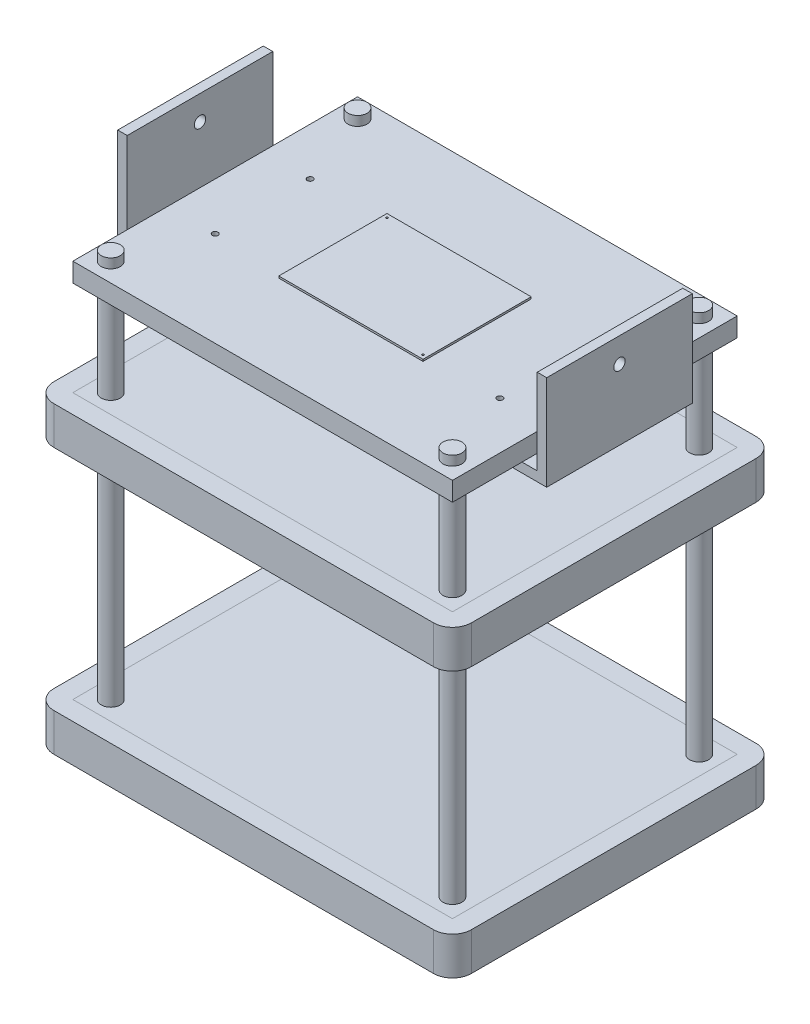
SolidWorks part; units mm, degrees
ref_plane "Front Plane" through (0, 0, 0) normal (0, 0, 1) x (1, 0, 0)
ref_plane "Top Plane" through (0, 0, 0) normal (0, 1, 0) x (1, 0, 0)
ref_plane "Right Plane" through (0, 0, 0) normal (1, 0, 0) x (0, 0, -1)
sketch "Sketch1" plane through (0, 0, 0) normal (0, 1, 0) x (1, 0, 0)
  line L1 (-100, 75) -> (100, 75)
  line L2 (-100, 75) -> (-100, -75)
  line L3 (-100, -75) -> (100, -75)
  line L4 (100, 75) -> (100, -75)
  line L5 (-100, 75) -> (100, -75) construction
  line L6 (-100, -75) -> (100, 75) construction
  point P0 (0, 0)
  dimension "D1" = 200
  dimension "D2" = 150
extrude "Boss-Extrude1" add sketch "Sketch1" along normal blind 10
sketch "Sketch2" plane through (0, 10, 0) normal (0, 1, 0) x (1, 0, 0)
  line L0 (-100, 75) -> (-100, -75) construction
  line L1 (100, 75) -> (-100, 75) construction
  line L2 (0, 73.0671) -> (0, 83.6614) construction
  line L3 (0, 83.6614) -> (0, -94.4748) construction
  line L4 (-110.8687, 0) -> (113.9791, 0) construction
  circle A0 centre (-90, 65) radius 5
  circle A1 centre (90, 65) radius 5
  circle A2 centre (90, -65) radius 5
  circle A3 centre (-90, -65) radius 5
  dimension "D1" = 10
  dimension "D2" = 10
  dimension "D3" = 10
extrude "Cut-Extrude1" cut sketch "Sketch2" against normal blind 10
ref_plane "Plane1" through (0, 140, 0) normal (0, 1, 0) x (1, 0, 0)
sketch "Sketch3" plane through (0, 140, 0) normal (0, 1, 0) x (1, 0, 0)
  line L1 (-100, 75) -> (100, 75)
  line L2 (-100, 75) -> (-100, -75)
  line L3 (-100, -75) -> (100, -75)
  line L4 (100, 75) -> (100, -75)
  line L5 (-100, 75) -> (100, -75) construction
  line L6 (-100, -75) -> (100, 75) construction
  circle A0 centre (-90, 65) radius 5
  circle A1 centre (90, 65) radius 5
  circle A2 centre (-90, -65) radius 5
  circle A3 centre (90, -65) radius 5
  point P0 (0, 0)
extrude "Boss-Extrude2" add sketch "Sketch3" along normal blind 10 separate body
ref_plane "Plane4" through (0, 200, 0) normal (0, 1, 0) x (1, 0, 0)
sketch "Sketch4" plane through (0, 200, 0) normal (0, 1, 0) x (1, 0, 0)
  line L1 (-100, 75) -> (100, 75)
  line L2 (-100, 75) -> (-100, -75)
  line L3 (-100, -75) -> (100, -75)
  line L4 (100, 75) -> (100, -75)
  line L5 (-100, 75) -> (100, -75) construction
  line L6 (-100, -75) -> (100, 75) construction
  circle A0 centre (-90, 65) radius 5
  circle A1 centre (90, 65) radius 5
  circle A2 centre (90, -65) radius 5
  circle A3 centre (-90, -65) radius 5
  point P1 (0, 0)
extrude "Boss-Extrude3" add sketch "Sketch4" along normal blind 10 separate body
sketch "Sketch5" plane through (0, 210, 0) normal (0, 1, 0) x (1, 0, 0)
  circle A0 centre (-90, -65) radius 5
sketch "Sketch17" plane through (0, 200, 0) normal (0, -1, 0) x (1, 0, 0)
  circle A0 centre (-90, -65) radius 5.3637
sketch "Sketch21" plane through (0, 10, 0) normal (0, 1, 0) x (1, 0, 0)
  circle A0 centre (-90, -65) radius 5
  circle A1 centre (-90, 65) radius 5
  circle A2 centre (90, 65) radius 5
  circle A3 centre (90, -65) radius 5
  dimension "D1" = 10
  dimension "D2" = 10
  dimension "D3" = 10
  dimension "D4" = 10
extrude "Boss-Extrude13" add sketch "Sketch21" along normal blind 205
sketch "Sketch22" plane through (0, 10, 0) normal (0, 1, 0) x (1, 0, 0)
  circle A0 centre (-90, 65) radius 5
  circle A1 centre (-90, -65) radius 5
  circle A2 centre (90, -65) radius 5
  circle A3 centre (90, 65) radius 5
  dimension "D1" = 10
  dimension "D2" = 10
  dimension "D3" = 10
  dimension "D4" = 10
extrude "Boss-Extrude14" add sketch "Sketch22" against normal blind 15
sketch "Sketch23" plane through (0, 210, 0) normal (0, 1, 0) x (1, 0, 0)
  line L0 (-100, 75) -> (-100, -75) construction
  line L1 (-140.155, 0) -> (119.4256, 0) construction
  line L2 (0, -82.5) -> (0, 82.5) construction
  circle A0 centre (-75, 25) radius 1.5
  circle A1 centre (-75, -25) radius 1.5
  circle A2 centre (75, -25) radius 1.5
  circle A3 centre (75, 25) radius 1.5
  dimension "D1" = 3
  dimension "D2" = 25
  dimension "D3" = 25
extrude "Cut-Extrude2" cut sketch "Sketch23" against normal blind 10
sketch "Sketch27" plane through (0, 210, 0) normal (0, 1, 0) x (1, 0, 0)
  line L0 (-38, 28.5) -> (38, -28.5) construction
  line L5 (-38, -28.5) -> (38, 28.5) construction
  line L7 (-38, 28.5) -> (38, 28.5)
  line L8 (-38, 28.5) -> (-38, -28.5)
  line L9 (-38, -28.5) -> (38, -28.5)
  line L10 (38, 28.5) -> (38, -28.5)
  circle A0 centre (-36, 26.5) radius 0.5
  circle A1 centre (36, -26.5) radius 0.5
  point P0 (-6.164, -10.787)
  point P5 (0, 0)
  point P11 (0, 0)
  dimension "D3" = 1
  dimension "D6" = 1
  dimension "D1" = 57
  dimension "D2" = 76
  dimension "D4" = 2
  dimension "D5" = 2
  dimension "D7" = 2
  dimension "D8" = 2
extrude "Boss-Extrude16" add sketch "Sketch27" along normal blind 1 contours L8 L7 L10 L9
sketch "Sketch30" plane through (0, 211, 0) normal (0, 1, 0) x (1, 0, 0)
  line L0 (-38, 28.5) -> (-38, -28.5) construction
  line L1 (-38, 28.5) -> (38, 28.5) construction
  line L2 (38, 28.5) -> (38, -28.5) construction
  line L3 (-38, -28.5) -> (38, -28.5) construction
  circle A0 centre (-36, 26.5) radius 0.5
  circle A1 centre (36, -26.5) radius 0.5
  dimension "D1" = 1
  dimension "D4" = 1
  dimension "D2" = 2
  dimension "D3" = 2
  dimension "D5" = 2
  dimension "D6" = 2
extrude "Cut-Extrude3" cut sketch "Sketch30" against normal blind 30
sketch "Sketch35" plane through (0, 0, 0) normal (0, -1, 0) x (-1, 0, 0)
  line L1 (100, -75) -> (-100, -75)
  line L2 (100, -75) -> (100, 75)
  line L3 (100, 75) -> (-100, 75)
  line L4 (-100, -75) -> (-100, 75)
  line L5 (100, -75) -> (-100, 75) construction
  line L6 (100, 75) -> (-100, -75) construction
  line L7 (110, -85) -> (-110, -85)
  line L8 (110, -85) -> (110, 85)
  line L9 (110, 85) -> (-110, 85)
  line L10 (-110, -85) -> (-110, 85)
  line L11 (110, -85) -> (-110, 85) construction
  line L12 (110, 85) -> (-110, -85) construction
  point P0 (0, 0)
  point P6 (0, 0)
  dimension "D1" = 150
  dimension "D2" = 170
  dimension "D3" = 200
  dimension "D4" = 220
extrude "Boss-Extrude19" add sketch "Sketch35" along normal mid plane 20 separate body
fillet "Fillet4" radius 10 4 edges at (110, 0, 85) (110, 0, -85) (-110, 0, 85) (-110, 0, -85)
sketch "Sketch39" plane through (0, 140, 0) normal (0, -1, 0) x (1, 0, 0)
  line L1 (-100, 75) -> (100, 75)
  line L2 (-100, 75) -> (-100, -75)
  line L3 (-100, -75) -> (100, -75)
  line L4 (100, 75) -> (100, -75)
  line L5 (-100, 75) -> (100, -75) construction
  line L6 (-100, -75) -> (100, 75) construction
  line L7 (-110, 85) -> (110, 85)
  line L8 (-110, 85) -> (-110, -85)
  line L9 (-110, -85) -> (110, -85)
  line L10 (110, 85) -> (110, -85)
  line L11 (-110, 85) -> (110, -85) construction
  line L12 (-110, -85) -> (110, 85) construction
  point P0 (0, 0)
  point P6 (0, 0)
  dimension "D1" = 150
  dimension "D2" = 200
  dimension "D3" = 170
  dimension "D4" = 220
extrude "Boss-Extrude20" add sketch "Sketch39" along normal mid plane 20 separate body
fillet "Fillet5" radius 10 4 edges at (110, 140, 85) (110, 140, -85) (-110, 140, -85) (-110, 140, 85)
sketch "Sketch42" plane through (0, 200, 0) normal (0, -1, 0) x (1, 0, 0)
  line L1 (-7.5, 10) -> (7.5, 10)
  line L2 (-7.5, 10) -> (-7.5, -10)
  line L3 (-7.5, -10) -> (7.5, -10)
  line L4 (7.5, 10) -> (7.5, -10)
  line L5 (-7.5, 10) -> (7.5, -10) construction
  line L6 (-7.5, -10) -> (7.5, 10) construction
  line L7 (-70.7403, -32.1967) -> (-15.7403, -32.1967)
  line L8 (-70.7403, -32.1967) -> (-70.7403, 32.8033)
  line L9 (-70.7403, 32.8033) -> (-15.7403, 32.8033)
  line L10 (-15.7403, -32.1967) -> (-15.7403, 32.8033)
  line L11 (-70.7403, -32.1967) -> (-15.7403, 32.8033) construction
  line L12 (-70.7403, 32.8033) -> (-15.7403, -32.1967) construction
  line L13 (15.7, 23.8618) -> (59, 23.8618)
  line L14 (15.7, 23.8618) -> (15.7, -19.4382)
  line L15 (15.7, -19.4382) -> (59, -19.4382)
  line L16 (59, 23.8618) -> (59, -19.4382)
  line L17 (15.7, 23.8618) -> (59, -19.4382) construction
  line L18 (15.7, -19.4382) -> (59, 23.8618) construction
  point P0 (0, 0)
  point P6 (-43.2403, 0.3033)
  point P11 (37.35, 2.2118)
  dimension "D1" = 20
  dimension "D2" = 15
  dimension "D3" = 65
  dimension "D4" = 55
  dimension "D5" = 43.3
  dimension "D6" = 43.3
  dimension "D7" = 8.2
extrude "Boss-Extrude23" add sketch "Sketch42" along normal blind 1
sketch "Sketch46" plane through (0, 200, 0) normal (0, -1, 0) x (-1, 0, 0)
  line L0 (-196.0871, 0) -> (303.0775, 0) construction
  line L5 (100, -75) -> (100, 75) construction
  line L6 (0, 93.5) -> (0, -93.5) construction
  line L7 (-108, 38.3353) -> (-108, -38.3353)
  line L8 (78, 38.3353) -> (108, 38.3353)
  line L9 (78, 38.3353) -> (78, -38.3353)
  line L10 (78, -38.3353) -> (108, -38.3353)
  line L11 (108, 38.3353) -> (108, -38.3353)
  line L12 (78, 38.3353) -> (108, -38.3353) construction
  line L13 (78, -38.3353) -> (108, 38.3353) construction
  line L14 (-78, -38.3353) -> (-108, -38.3353)
  line L15 (-78, 38.3353) -> (-78, -38.3353)
  line L16 (-78, 38.3353) -> (-108, 38.3353)
  point P0 (122.8294, -19.1676)
  point P6 (93, 0)
  dimension "D1" = 22
  dimension "D2" = 30
extrude "Boss-Extrude24" add sketch "Sketch46" along normal blind 5
sketch "Sketch48" plane through (-108, 0, 0) normal (-1, 0, 0) x (0, 0, 1)
  line L0 (93.5, 0) -> (-93.5, 0) construction
  line L1 (-38.3353, 195) -> (38.3353, 195)
  line L2 (-38.3353, 195) -> (-38.3353, 245)
  line L3 (-38.3353, 245) -> (38.3353, 245)
  line L4 (38.3353, 195) -> (38.3353, 245)
  dimension "D1" = 50
extrude "Boss-Extrude25" add sketch "Sketch48" along normal blind 5
sketch "Sketch49" plane through (-113, 0, 0) normal (-1, 0, 0) x (0, 0, 1)
  line L1 (-38.3353, 195) -> (38.3353, 195) construction
  circle A0 centre (0, 232) radius 3
  dimension "D2" = 6
  dimension "D1" = 37
extrude "Cut-Extrude4" cut sketch "Sketch49" against normal blind 5
sketch "Sketch54" plane through (108, 0, 0) normal (1, 0, 0) x (0, 0, -1)
  line L1 (-38.3353, 195) -> (38.3353, 195)
  line L2 (-38.3353, 195) -> (-38.3353, 245)
  line L3 (-38.3353, 245) -> (38.3353, 245)
  line L4 (38.3353, 195) -> (38.3353, 245)
  point P6 (34.4946, 241.7874)
extrude "Boss-Extrude26" add sketch "Sketch54" along normal blind 5
sketch "Sketch55" plane through (113, 0, 0) normal (1, 0, 0) x (0, 0, -1)
  line L0 (-38.3353, 195) -> (38.3353, 195) construction
  circle A0 centre (0, 232) radius 3
  dimension "D1" = 6
  dimension "D2" = 37
extrude "Cut-Extrude5" cut sketch "Sketch55" against normal blind 5
